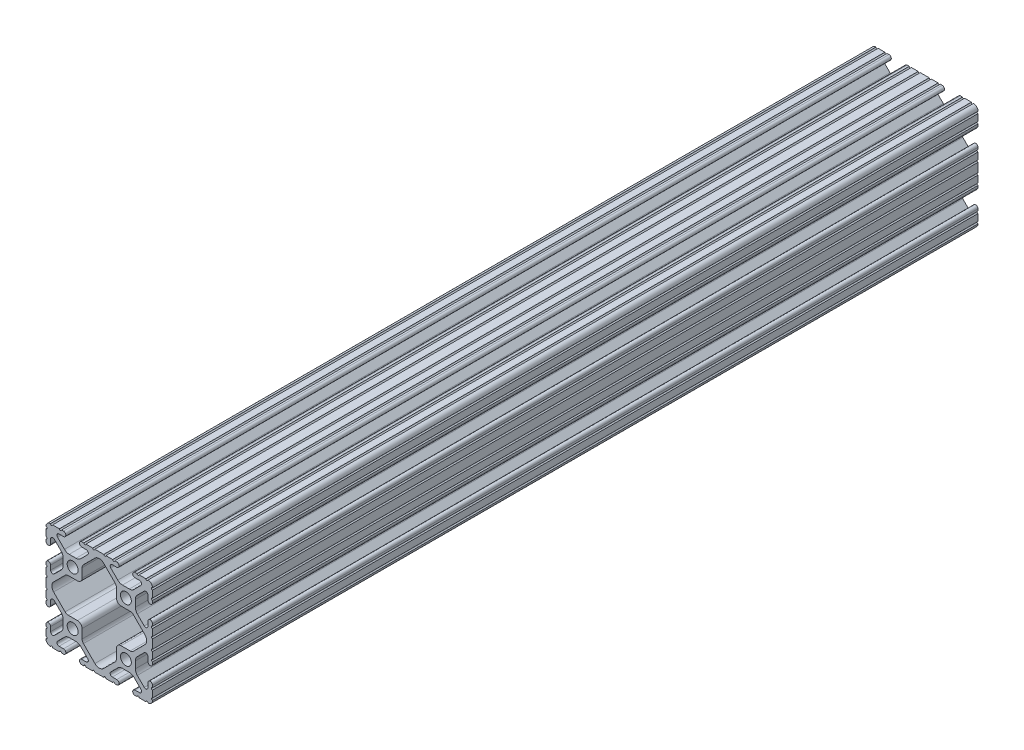
SolidWorks part; units mm, degrees
material "6063-T6"
ref_plane "Front Plane" through (0, 0, 0) normal (0, 0, 1) x (1, 0, 0)
ref_plane "Top Plane" through (0, 0, 0) normal (0, 1, 0) x (1, 0, 0)
ref_plane "Right Plane" through (0, 0, 0) normal (1, 0, 0) x (0, 0, -1)
sketch "Sketch1" plane through (0, 0, 0) normal (0, 0, 1) x (1, 0, 0)
  line L0 (-10.4013, 8.1915) -> (-14.7306, 8.1915)
  line L1 (-16.2932, 7.5443) -> (-21.772, 2.0655)
  line L2 (-21.772, -2.0655) -> (-16.2932, -7.5443)
  line L3 (-14.7306, -8.1915) -> (-10.4013, -8.1915)
  line L4 (-8.1915, -10.4013) -> (-8.1915, -14.7306)
  line L5 (-7.5443, -16.2932) -> (-2.0655, -21.772)
  line L6 (2.0655, -21.772) -> (7.5443, -16.2932)
  line L7 (8.1915, -14.7306) -> (8.1915, -10.4013)
  line L8 (10.4013, -8.1915) -> (14.7306, -8.1915)
  line L9 (16.2932, -7.5443) -> (21.772, -2.0655)
  line L10 (21.772, 2.0655) -> (16.2932, 7.5443)
  line L11 (14.7306, 8.1915) -> (10.4013, 8.1915)
  line L12 (8.1915, 10.4013) -> (8.1915, 14.7306)
  line L13 (7.5443, 16.2932) -> (2.0655, 21.772)
  line L14 (-2.0655, 21.772) -> (-7.5443, 16.2932)
  line L15 (-8.1915, 14.7306) -> (-8.1915, 10.4013)
  line L16 (-2.1336, -25.4) -> (2.1336, -25.4)
  line L17 (3.1496, -25.4) -> (6.3754, -25.4)
  line L18 (7.3914, -25.4) -> (8.3439, -25.4)
  line L19 (8.3439, -23.1902) -> (6.2252, -23.1902)
  line L20 (5.5068, -21.4558) -> (8.8241, -18.1384)
  line L21 (11.0692, -17.2085) -> (14.3308, -17.2085)
  line L22 (16.5759, -18.1384) -> (19.8932, -21.4558)
  line L23 (19.1748, -23.1902) -> (17.0561, -23.1902)
  line L24 (17.0561, -25.4) -> (18.0086, -25.4)
  line L25 (19.0246, -25.4) -> (22.2504, -25.4)
  line L26 (23.2664, -25.4) -> (23.2918, -25.4)
  line L27 (25.4, -23.2918) -> (25.4, -23.2664)
  line L28 (25.4, -22.2504) -> (25.4, -19.0246)
  line L29 (25.4, -18.0086) -> (25.4, -17.0561)
  line L30 (23.1902, -17.0561) -> (23.1902, -19.1748)
  line L31 (21.4558, -19.8932) -> (18.1384, -16.5759)
  line L32 (17.2085, -14.3308) -> (17.2085, -11.0692)
  line L33 (18.1384, -8.8241) -> (21.4558, -5.5068)
  line L34 (23.1902, -6.2252) -> (23.1902, -8.3439)
  line L35 (25.4, -8.3439) -> (25.4, -7.3914)
  line L36 (25.4, -6.3754) -> (25.4, -3.1496)
  line L37 (25.4, -2.1336) -> (25.4, 2.1336)
  line L38 (25.4, 3.1496) -> (25.4, 6.3754)
  line L39 (25.4, 7.3914) -> (25.4, 8.3439)
  line L40 (23.1902, 8.3439) -> (23.1902, 6.2252)
  line L41 (21.4558, 5.5068) -> (18.1384, 8.8241)
  line L42 (17.2085, 11.0692) -> (17.2085, 14.3308)
  line L43 (18.1384, 16.5759) -> (21.4558, 19.8932)
  line L44 (23.1902, 19.1748) -> (23.1902, 17.0561)
  line L45 (25.4, 17.0561) -> (25.4, 18.0086)
  line L46 (25.4, 19.0246) -> (25.4, 22.2504)
  line L47 (25.4, 23.2664) -> (25.4, 23.2918)
  line L48 (23.2918, 25.4) -> (23.2664, 25.4)
  line L49 (22.2504, 25.4) -> (19.0246, 25.4)
  line L50 (18.0086, 25.4) -> (17.0561, 25.4)
  line L51 (17.0561, 23.1902) -> (19.1748, 23.1902)
  line L52 (19.8932, 21.4558) -> (16.5759, 18.1384)
  line L53 (14.3308, 17.2085) -> (11.0692, 17.2085)
  line L54 (8.8241, 18.1384) -> (5.5068, 21.4558)
  line L55 (6.2252, 23.1902) -> (8.3439, 23.1902)
  line L56 (8.3439, 25.4) -> (7.3914, 25.4)
  line L57 (6.3754, 25.4) -> (3.1496, 25.4)
  line L58 (2.1336, 25.4) -> (-2.1336, 25.4)
  line L59 (-3.1496, 25.4) -> (-6.3754, 25.4)
  line L60 (-7.3914, 25.4) -> (-8.3439, 25.4)
  line L61 (-8.3439, 23.1902) -> (-6.2252, 23.1902)
  line L62 (-5.5068, 21.4558) -> (-8.8241, 18.1384)
  line L63 (-11.0692, 17.2085) -> (-14.3308, 17.2085)
  line L64 (-16.5759, 18.1384) -> (-19.8932, 21.4558)
  line L65 (-19.1748, 23.1902) -> (-17.0561, 23.1902)
  line L66 (-17.0561, 25.4) -> (-18.0086, 25.4)
  line L67 (-19.0246, 25.4) -> (-22.2504, 25.4)
  line L68 (-23.2664, 25.4) -> (-23.2918, 25.4)
  line L69 (-25.4, 23.2918) -> (-25.4, 23.2664)
  line L70 (-25.4, 22.2504) -> (-25.4, 19.0246)
  line L71 (-25.4, 18.0086) -> (-25.4, 17.0561)
  line L72 (-23.1902, 17.0561) -> (-23.1902, 19.1748)
  line L73 (-21.4558, 19.8932) -> (-18.1384, 16.5759)
  line L74 (-17.2085, 14.3308) -> (-17.2085, 11.0692)
  line L75 (-18.1384, 8.8241) -> (-21.4558, 5.5068)
  line L76 (-23.1902, 6.2252) -> (-23.1902, 8.3439)
  line L77 (-25.4, 8.3439) -> (-25.4, 7.3914)
  line L78 (-25.4, 6.3754) -> (-25.4, 3.1496)
  line L79 (-25.4, 2.1336) -> (-25.4, -2.1336)
  line L80 (-25.4, -3.1496) -> (-25.4, -6.3754)
  line L81 (-25.4, -7.3914) -> (-25.4, -8.3439)
  line L82 (-23.1902, -8.3439) -> (-23.1902, -6.2252)
  line L83 (-21.4558, -5.5068) -> (-18.1384, -8.8241)
  line L84 (-17.2085, -11.0692) -> (-17.2085, -14.3308)
  line L85 (-18.1384, -16.5759) -> (-21.4558, -19.8932)
  line L86 (-23.1902, -19.1748) -> (-23.1902, -17.0561)
  line L87 (-25.4, -17.0561) -> (-25.4, -18.0086)
  line L88 (-25.4, -19.0246) -> (-25.4, -22.2504)
  line L89 (-25.4, -23.2664) -> (-25.4, -23.2918)
  line L90 (-23.2918, -25.4) -> (-23.2664, -25.4)
  line L91 (-22.2504, -25.4) -> (-19.0246, -25.4)
  line L92 (-18.0086, -25.4) -> (-17.0561, -25.4)
  line L93 (-17.0561, -23.1902) -> (-19.1748, -23.1902)
  line L94 (-19.8932, -21.4558) -> (-16.5759, -18.1384)
  line L95 (-14.3308, -17.2085) -> (-11.0692, -17.2085)
  line L96 (-8.8241, -18.1384) -> (-5.5068, -21.4558)
  line L97 (-6.2252, -23.1902) -> (-8.3439, -23.1902)
  line L98 (-8.3439, -25.4) -> (-7.3914, -25.4)
  line L99 (-6.3754, -25.4) -> (-3.1496, -25.4)
  arc A0 (-14.7306, 8.1915) -> (-16.2932, 7.5443) centre (-14.7306, 5.9817) ccw
  arc A1 (-21.772, 2.0655) -> (-21.772, -2.0655) centre (-19.7065, 0) ccw
  arc A2 (-16.2932, -7.5443) -> (-14.7306, -8.1915) centre (-14.7306, -5.9817) ccw
  arc A3 (-8.1915, -10.4013) -> (-10.4013, -8.1915) centre (-10.4013, -10.4013) ccw
  arc A4 (-8.1915, -14.7306) -> (-7.5443, -16.2932) centre (-5.9817, -14.7306) ccw
  arc A5 (-2.0655, -21.772) -> (2.0655, -21.772) centre (0, -19.7065) ccw
  arc A6 (7.5443, -16.2932) -> (8.1915, -14.7306) centre (5.9817, -14.7306) ccw
  arc A7 (10.4013, -8.1915) -> (8.1915, -10.4013) centre (10.4013, -10.4013) ccw
  arc A8 (14.7306, -8.1915) -> (16.2932, -7.5443) centre (14.7306, -5.9817) ccw
  arc A9 (21.772, -2.0655) -> (21.772, 2.0655) centre (19.7065, 0) ccw
  arc A10 (16.2932, 7.5443) -> (14.7306, 8.1915) centre (14.7306, 5.9817) ccw
  arc A11 (8.1915, 10.4013) -> (10.4013, 8.1915) centre (10.4013, 10.4013) ccw
  arc A12 (8.1915, 14.7306) -> (7.5443, 16.2932) centre (5.9817, 14.7306) ccw
  arc A13 (2.0655, 21.772) -> (-2.0655, 21.772) centre (0, 19.7065) ccw
  arc A14 (-7.5443, 16.2932) -> (-8.1915, 14.7306) centre (-5.9817, 14.7306) ccw
  arc A15 (-10.4013, 8.1915) -> (-8.1915, 10.4013) centre (-10.4013, 10.4013) ccw
  arc A16 (-2.1336, -25.4) -> (-3.1496, -25.4) centre (-2.6416, -25.4) ccw
  arc A17 (3.1496, -25.4) -> (2.1336, -25.4) centre (2.6416, -25.4) ccw
  arc A18 (7.3914, -25.4) -> (6.3754, -25.4) centre (6.8834, -25.4) ccw
  arc A19 (8.3439, -25.4) -> (8.3439, -23.1902) centre (8.3439, -24.2951) ccw
  arc A20 (5.5068, -21.4558) -> (6.2252, -23.1902) centre (6.2252, -22.1742) ccw
  arc A21 (11.0692, -17.2085) -> (8.8241, -18.1384) centre (11.0692, -20.3835) ccw
  arc A22 (16.5759, -18.1384) -> (14.3308, -17.2085) centre (14.3308, -20.3835) ccw
  arc A23 (19.1748, -23.1902) -> (19.8932, -21.4558) centre (19.1748, -22.1742) ccw
  arc A24 (17.0561, -23.1902) -> (17.0561, -25.4) centre (17.0561, -24.2951) ccw
  arc A25 (19.0246, -25.4) -> (18.0086, -25.4) centre (18.5166, -25.4) ccw
  arc A26 (23.2664, -25.4) -> (22.2504, -25.4) centre (22.7584, -25.4) ccw
  arc A27 (23.2918, -25.4) -> (25.4, -23.2918) centre (23.2918, -23.2918) ccw
  arc A28 (25.4, -22.2504) -> (25.4, -23.2664) centre (25.4, -22.7584) ccw
  arc A29 (25.4, -18.0086) -> (25.4, -19.0246) centre (25.4, -18.5166) ccw
  arc A30 (25.4, -17.0561) -> (23.1902, -17.0561) centre (24.2951, -17.0561) ccw
  arc A31 (21.4558, -19.8932) -> (23.1902, -19.1748) centre (22.1742, -19.1748) ccw
  arc A32 (17.2085, -14.3308) -> (18.1384, -16.5759) centre (20.3835, -14.3308) ccw
  arc A33 (18.1384, -8.8241) -> (17.2085, -11.0692) centre (20.3835, -11.0692) ccw
  arc A34 (23.1902, -6.2252) -> (21.4558, -5.5068) centre (22.1742, -6.2252) ccw
  arc A35 (23.1902, -8.3439) -> (25.4, -8.3439) centre (24.2951, -8.3439) ccw
  arc A36 (25.4, -6.3754) -> (25.4, -7.3914) centre (25.4, -6.8834) ccw
  arc A37 (25.4, -2.1336) -> (25.4, -3.1496) centre (25.4, -2.6416) ccw
  arc A38 (25.4, 3.1496) -> (25.4, 2.1336) centre (25.4, 2.6416) ccw
  arc A39 (25.4, 7.3914) -> (25.4, 6.3754) centre (25.4, 6.8834) ccw
  arc A40 (25.4, 8.3439) -> (23.1902, 8.3439) centre (24.2951, 8.3439) ccw
  arc A41 (21.4558, 5.5068) -> (23.1902, 6.2252) centre (22.1742, 6.2252) ccw
  arc A42 (17.2085, 11.0692) -> (18.1384, 8.8241) centre (20.3835, 11.0692) ccw
  arc A43 (18.1384, 16.5759) -> (17.2085, 14.3308) centre (20.3835, 14.3308) ccw
  arc A44 (23.1902, 19.1748) -> (21.4558, 19.8932) centre (22.1742, 19.1748) ccw
  arc A45 (23.1902, 17.0561) -> (25.4, 17.0561) centre (24.2951, 17.0561) ccw
  arc A46 (25.4, 19.0246) -> (25.4, 18.0086) centre (25.4, 18.5166) ccw
  arc A47 (25.4, 23.2664) -> (25.4, 22.2504) centre (25.4, 22.7584) ccw
  arc A48 (25.4, 23.2918) -> (23.2918, 25.4) centre (23.2918, 23.2918) ccw
  arc A49 (22.2504, 25.4) -> (23.2664, 25.4) centre (22.7584, 25.4) ccw
  arc A50 (18.0086, 25.4) -> (19.0246, 25.4) centre (18.5166, 25.4) ccw
  arc A51 (17.0561, 25.4) -> (17.0561, 23.1902) centre (17.0561, 24.2951) ccw
  arc A52 (19.8932, 21.4558) -> (19.1748, 23.1902) centre (19.1748, 22.1742) ccw
  arc A53 (14.3308, 17.2085) -> (16.5759, 18.1384) centre (14.3308, 20.3835) ccw
  arc A54 (8.8241, 18.1384) -> (11.0692, 17.2085) centre (11.0692, 20.3835) ccw
  arc A55 (6.2252, 23.1902) -> (5.5068, 21.4558) centre (6.2252, 22.1742) ccw
  arc A56 (8.3439, 23.1902) -> (8.3439, 25.4) centre (8.3439, 24.2951) ccw
  arc A57 (6.3754, 25.4) -> (7.3914, 25.4) centre (6.8834, 25.4) ccw
  arc A58 (2.1336, 25.4) -> (3.1496, 25.4) centre (2.6416, 25.4) ccw
  arc A59 (-3.1496, 25.4) -> (-2.1336, 25.4) centre (-2.6416, 25.4) ccw
  arc A60 (-7.3914, 25.4) -> (-6.3754, 25.4) centre (-6.8834, 25.4) ccw
  arc A61 (-8.3439, 25.4) -> (-8.3439, 23.1902) centre (-8.3439, 24.2951) ccw
  arc A62 (-5.5068, 21.4558) -> (-6.2252, 23.1902) centre (-6.2252, 22.1742) ccw
  arc A63 (-11.0692, 17.2085) -> (-8.8241, 18.1384) centre (-11.0692, 20.3835) ccw
  arc A64 (-16.5759, 18.1384) -> (-14.3308, 17.2085) centre (-14.3308, 20.3835) ccw
  arc A65 (-19.1748, 23.1902) -> (-19.8932, 21.4558) centre (-19.1748, 22.1742) ccw
  arc A66 (-17.0561, 23.1902) -> (-17.0561, 25.4) centre (-17.0561, 24.2951) ccw
  arc A67 (-19.0246, 25.4) -> (-18.0086, 25.4) centre (-18.5166, 25.4) ccw
  arc A68 (-23.2664, 25.4) -> (-22.2504, 25.4) centre (-22.7584, 25.4) ccw
  arc A69 (-23.2918, 25.4) -> (-25.4, 23.2918) centre (-23.2918, 23.2918) ccw
  arc A70 (-25.4, 22.2504) -> (-25.4, 23.2664) centre (-25.4, 22.7584) ccw
  arc A71 (-25.4, 18.0086) -> (-25.4, 19.0246) centre (-25.4, 18.5166) ccw
  arc A72 (-25.4, 17.0561) -> (-23.1902, 17.0561) centre (-24.2951, 17.0561) ccw
  arc A73 (-21.4558, 19.8932) -> (-23.1902, 19.1748) centre (-22.1742, 19.1748) ccw
  arc A74 (-17.2085, 14.3308) -> (-18.1384, 16.5759) centre (-20.3835, 14.3308) ccw
  arc A75 (-18.1384, 8.8241) -> (-17.2085, 11.0692) centre (-20.3835, 11.0692) ccw
  arc A76 (-23.1902, 6.2252) -> (-21.4558, 5.5068) centre (-22.1742, 6.2252) ccw
  arc A77 (-23.1902, 8.3439) -> (-25.4, 8.3439) centre (-24.2951, 8.3439) ccw
  arc A78 (-25.4, 6.3754) -> (-25.4, 7.3914) centre (-25.4, 6.8834) ccw
  arc A79 (-25.4, 2.1336) -> (-25.4, 3.1496) centre (-25.4, 2.6416) ccw
  arc A80 (-25.4, -3.1496) -> (-25.4, -2.1336) centre (-25.4, -2.6416) ccw
  arc A81 (-25.4, -7.3914) -> (-25.4, -6.3754) centre (-25.4, -6.8834) ccw
  arc A82 (-25.4, -8.3439) -> (-23.1902, -8.3439) centre (-24.2951, -8.3439) ccw
  arc A83 (-21.4558, -5.5068) -> (-23.1902, -6.2252) centre (-22.1742, -6.2252) ccw
  arc A84 (-17.2085, -11.0692) -> (-18.1384, -8.8241) centre (-20.3835, -11.0692) ccw
  arc A85 (-18.1384, -16.5759) -> (-17.2085, -14.3308) centre (-20.3835, -14.3308) ccw
  arc A86 (-23.1902, -19.1748) -> (-21.4558, -19.8932) centre (-22.1742, -19.1748) ccw
  arc A87 (-23.1902, -17.0561) -> (-25.4, -17.0561) centre (-24.2951, -17.0561) ccw
  arc A88 (-25.4, -19.0246) -> (-25.4, -18.0086) centre (-25.4, -18.5166) ccw
  arc A89 (-25.4, -23.2664) -> (-25.4, -22.2504) centre (-25.4, -22.7584) ccw
  arc A90 (-25.4, -23.2918) -> (-23.2918, -25.4) centre (-23.2918, -23.2918) ccw
  arc A91 (-22.2504, -25.4) -> (-23.2664, -25.4) centre (-22.7584, -25.4) ccw
  arc A92 (-18.0086, -25.4) -> (-19.0246, -25.4) centre (-18.5166, -25.4) ccw
  arc A93 (-17.0561, -25.4) -> (-17.0561, -23.1902) centre (-17.0561, -24.2951) ccw
  arc A94 (-19.8932, -21.4558) -> (-19.1748, -23.1902) centre (-19.1748, -22.1742) ccw
  arc A95 (-14.3308, -17.2085) -> (-16.5759, -18.1384) centre (-14.3308, -20.3835) ccw
  arc A96 (-8.8241, -18.1384) -> (-11.0692, -17.2085) centre (-11.0692, -20.3835) ccw
  arc A97 (-6.2252, -23.1902) -> (-5.5068, -21.4558) centre (-6.2252, -22.1742) ccw
  arc A98 (-8.3439, -23.1902) -> (-8.3439, -25.4) centre (-8.3439, -24.2951) ccw
  arc A99 (-6.3754, -25.4) -> (-7.3914, -25.4) centre (-6.8834, -25.4) ccw
  circle A100 centre (12.7, 12.7) radius 2.6035
  circle A101 centre (12.7, -12.7) radius 2.6035
  circle A102 centre (-12.7, 12.7) radius 2.6035
  circle A103 centre (-12.7, -12.7) radius 2.6035
  dimension "D1" = 12.7
  dimension "D2" = 12.7
  dimension "D3" = 12.7
  dimension "D4" = 12.7
extrude "Extrude1" add sketch "Sketch1" along normal mid plane 393.7
